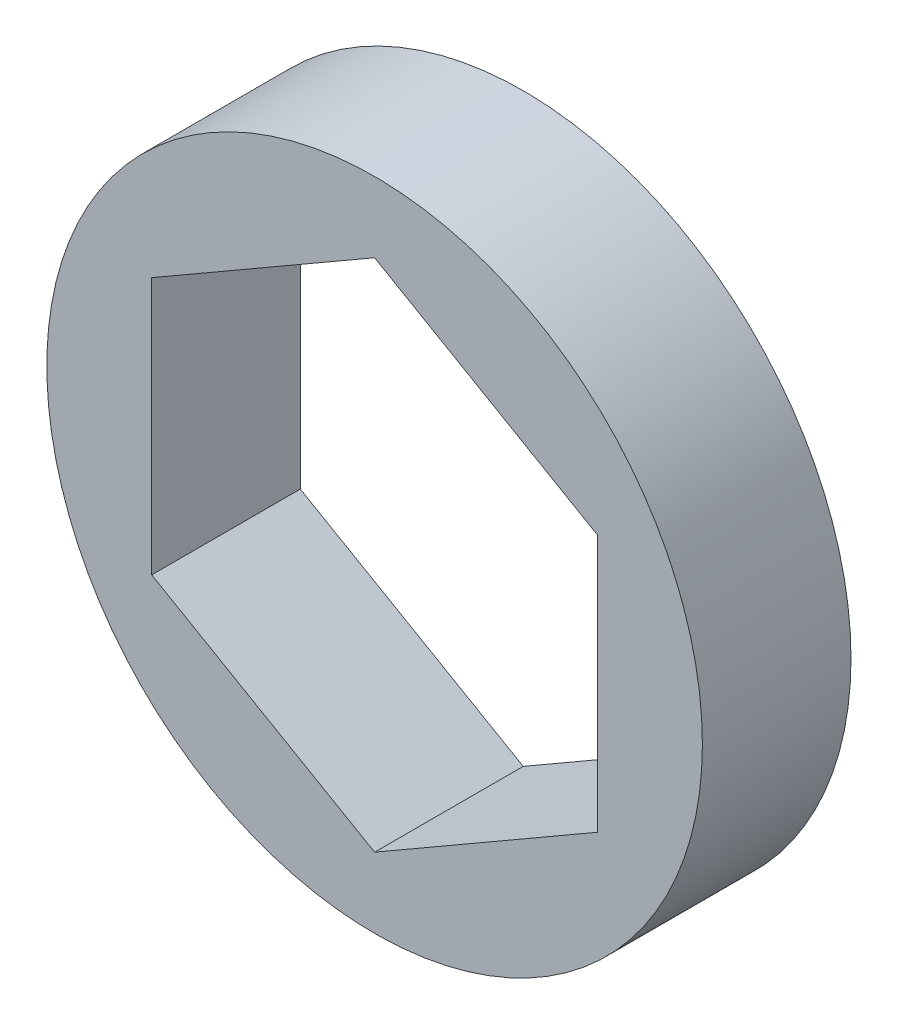
SolidWorks part; units mm, degrees
material "PET"
ref_plane "Front" through (0, 0, 0) normal (0, 0, 1) x (1, 0, 0)
ref_plane "Top" through (0, 0, 0) normal (0, 1, 0) x (1, 0, 0)
ref_plane "Right" through (0, 0, 0) normal (1, 0, 0) x (0, 0, -1)
sketch "Sketch1" plane through (0, 0, 0) normal (0, 0, 1) x (1, 0, 0)
  line L1 (0, 7.479) -> (-6.477, 3.7395)
  line L2 (-6.477, 3.7395) -> (-6.477, -3.7395)
  line L3 (-6.477, -3.7395) -> (0, -7.479)
  line L4 (0, -7.479) -> (6.477, -3.7395)
  line L5 (6.477, -3.7395) -> (6.477, 3.7395)
  line L6 (6.477, 3.7395) -> (0, 7.479)
  circle A0 centre (0, 0) radius 9.525
  circle A1 centre (0, 0) radius 6.477 construction
  dimension "D2" = 19.05
  dimension "D1" = 12.954
extrude "Boss-Extrude1" add sketch "Sketch1" along normal blind 4.318
